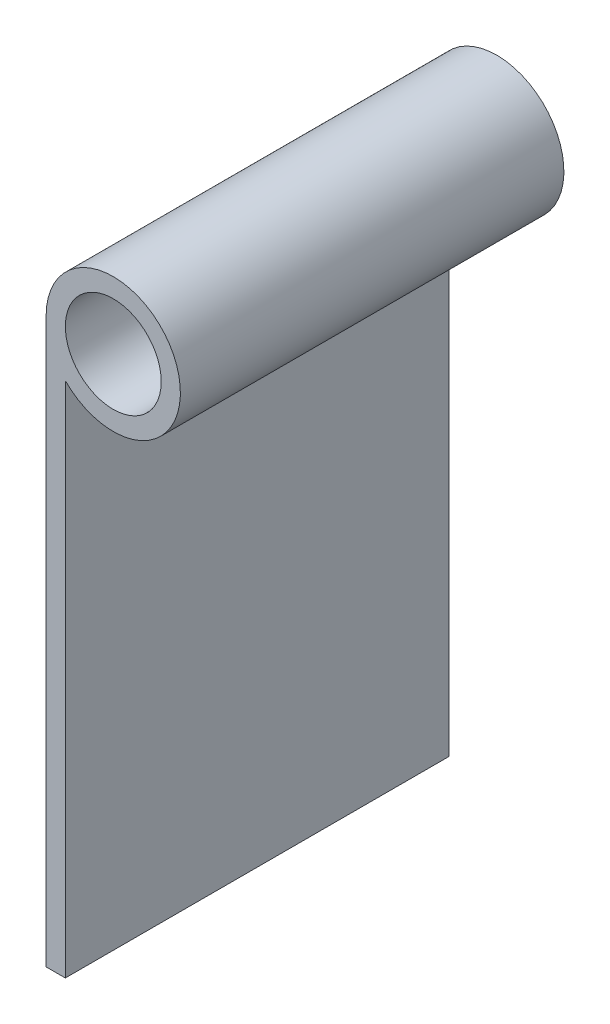
SolidWorks part; units mm, degrees
ref_plane "Front Plane" through (0, 0, 0) normal (0, 0, 1) x (1, 0, 0)
ref_plane "Top Plane" through (0, 0, 0) normal (0, 1, 0) x (1, 0, 0)
ref_plane "Right Plane" through (0, 0, 0) normal (1, 0, 0) x (0, 0, -1)
sketch "Sketch1" plane through (0, 0, 0) normal (0, 0, 1) x (1, 0, 0)
  line L0 (-8.89, 0) -> (-8.89, -74.7513)
  line L1 (-8.89, -74.7513) -> (-6.35, -74.7513)
  line L2 (-6.35, -74.7513) -> (-6.35, -6.2217)
  circle A0 centre (0, 0) radius 6.35
  arc A1 (-6.35, -6.2217) -> (-8.89, 0) centre (0, 0) ccw
  dimension "D1" = 2.54
  dimension "D2" = 12.7
  dimension "D3" = 2.54
extrude "Boss-Extrude1" add sketch "Sketch1" along normal blind 50.8
